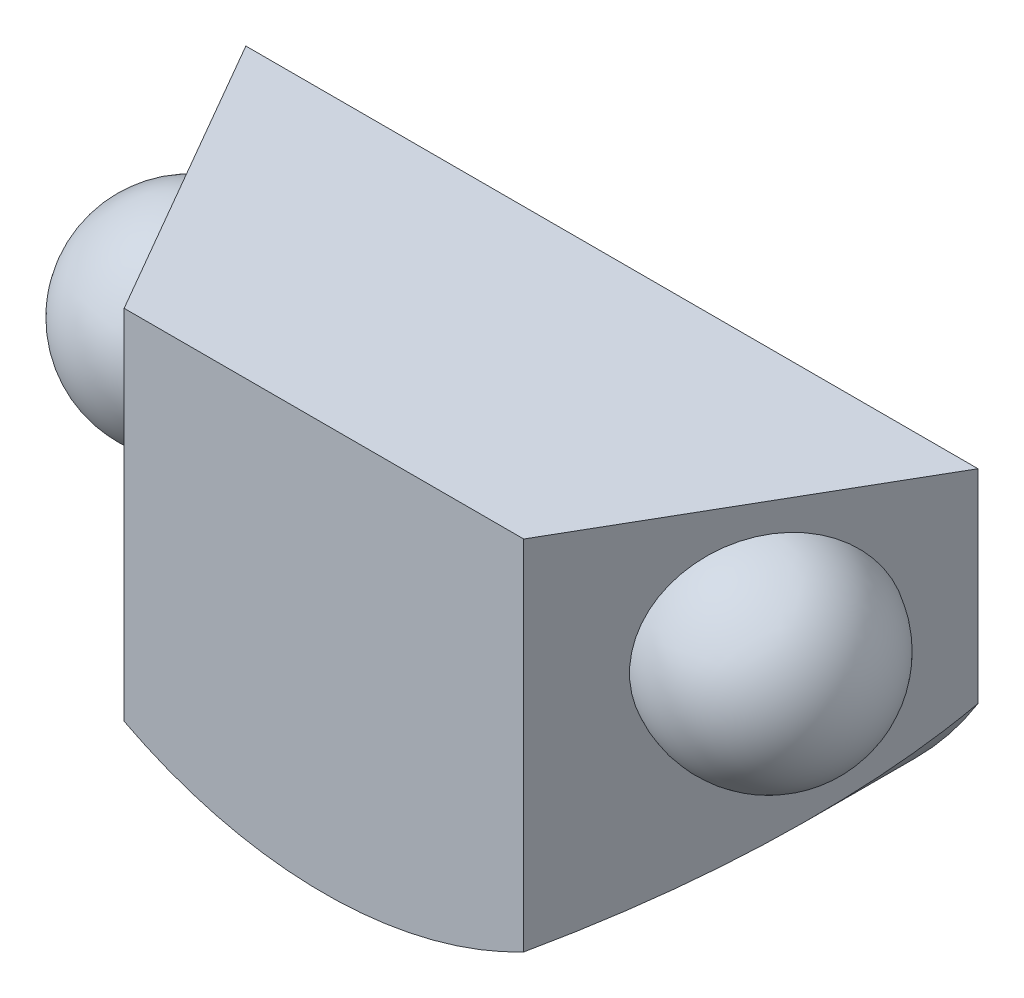
SolidWorks part; units mm, degrees
ref_plane "Front Plane" through (0, 0, 0) normal (0, 0, 1) x (1, 0, 0)
ref_plane "Top Plane" through (0, 0, 0) normal (0, 1, 0) x (1, 0, 0)
ref_plane "Right Plane" through (0, 0, 0) normal (1, 0, 0) x (0, 0, -1)
sketch "Sketch1" plane through (0, 0, 0) normal (0, 1, 0) x (1, 0, 0)
  line L1 (-90, -55) -> (90, -55)
  line L2 (-90, -55) -> (-90, 55)
  line L3 (-90, 55) -> (90, 55)
  line L4 (90, -55) -> (90, 55)
  line L5 (-90, -55) -> (90, 55) construction
  line L6 (-90, 55) -> (90, -55) construction
  point P0 (0, 0)
  dimension "D1" = 110
  dimension "D2" = 180
extrude "Boss-Extrude1" add sketch "Sketch1" along normal blind 50
sketch "Sketch2" plane through (-35, 0, -55) normal (0, 0, 1) x (1, 0, 0)
  line L2 (-55, 0) -> (125, 0) construction
  line L3 (-55, 0) -> (125, 0)
  arc A1 (-55, 0) -> (125, 0) centre (35, 56) ccw
  point P3 (35, -50)
  dimension "D1" = 50
extrude "Boss-Extrude2" add sketch "Sketch2" along normal up to surface (110 mm away) up to face at (0, 25, 55)
sketch "Sketch3" plane through (0, 50, 0) normal (0, 1, 0) x (1, 0, 0)
  line L0 (-49.1188, -55) -> (-90, 15.8083)
  line L1 (-90, -55) -> (90, -55) construction
  line L2 (-90, 55) -> (-90, -55) construction
  line L3 (-90, 15.8083) -> (-90, -55)
  line L4 (-90, -55) -> (-49.1188, -55)
  dimension "D1" = 30
extrude "Cut-Extrude1" cut sketch "Sketch3" against normal through all
mirror "Mirror1" about plane through (0, 0, 0) normal (1, 0, 0) of "Cut-Extrude1"
sketch "Sketch4" plane through (-60.6548, 0, 35.0191) normal (-0.866, 0, 0.5) x (0.5, 0, 0.866)
  line L0 (-20.9652, 42.9426) -> (-20.9652, -7.0574)
  arc A1 (-20.9652, 42.9426) -> (-20.9652, -7.0574) centre (-20.9652, 17.9426) cw
  dimension "D1" = 50
sketch "Sketch5" plane through (0, 0, -55) normal (0, 0, -1) x (-1, 0, 0)
  circle A0 centre (0, 0) radius 5
  dimension "D1" = 0
extrude "Boss-Extrude5" add sketch "Sketch5" along normal blind 10 and the other way blind 10
revolve "Revolve1" add sketch "Sketch4" angle 360 about L0
mirror "Mirror2" about plane through (0, 0, 0) normal (1, 0, 0) of "Revolve1"
sketch "Sketch6" plane through (0, 50, 0) normal (0, 1, 0) x (1, 0, 0)
  line L1 (-90, 15.8083) -> (90.2384, 15.8083)
  line L2 (-90, 15.8083) -> (-90, 71.5441)
  line L3 (-90, 71.5441) -> (90.2384, 71.5441)
  line L4 (90.2384, 15.8083) -> (90.2384, 71.5441)
extrude "Cut-Extrude2" cut sketch "Sketch6" against normal blind 125
